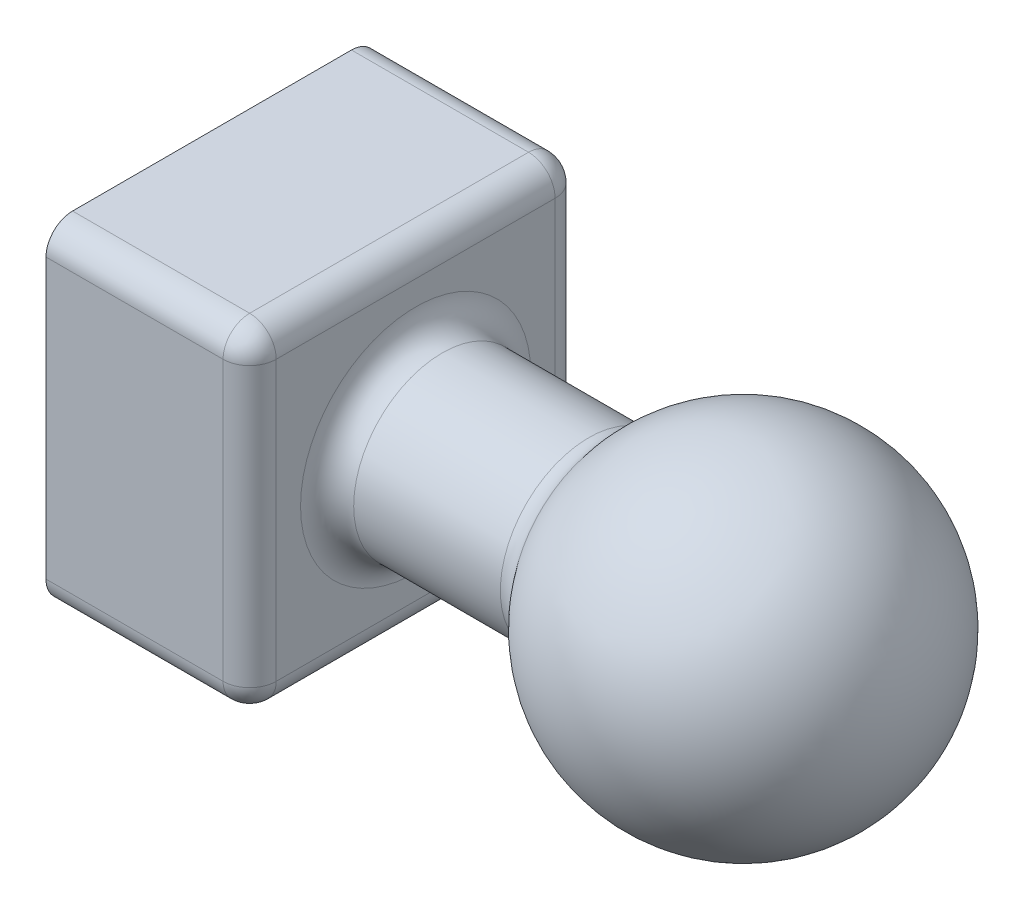
SolidWorks part; units mm, degrees
ref_plane "Front Plane" through (0, 0, 0) normal (0, 0, 1) x (1, 0, 0)
ref_plane "Top Plane" through (0, 0, 0) normal (0, 1, 0) x (1, 0, 0)
ref_plane "Right Plane" through (0, 0, 0) normal (1, 0, 0) x (0, 0, -1)
sketch "Sketch1" plane through (0, 0, 0) normal (0, 0, 1) x (1, 0, 0)
  line L0 (0, 0) -> (55.75, 0) construction
  line L1 (0, 0) -> (0, 10) construction
  line L2 (0, 10) -> (21.1393, 10)
  line L7 (0, 10) -> (0, 0)
  line L8 (0, 0) -> (55.75, 0)
  line L9 (55.75, 0) -> (-119.6805, 0) construction
  line L10 (37, 18.75) -> (-31.2433, 18.75) construction
  arc A0 (55.75, 0) -> (21.1393, 10) centre (37, 0) ccw
  point P7 (-3.7507, 10)
  point P12 (-4.1632, 18.75)
  point P13 (0, 0)
  point P14 (-0.4506, 10)
  dimension "D1" = 18.75
  dimension "D2" = 37
  dimension "D3" = 20
revolve "Revolve1" add sketch "Sketch1" angle 360 about L9
sketch "Sketch2" plane through (0, 0, 0) normal (-1, 0, 0) x (0, 0, 1)
  line L1 (-18.75, -18.75) -> (18.75, -18.75)
  line L2 (-18.75, -18.75) -> (-18.75, 18.75)
  line L3 (-18.75, 18.75) -> (18.75, 18.75)
  line L4 (18.75, -18.75) -> (18.75, 18.75)
  line L5 (-18.75, -18.75) -> (18.75, 18.75) construction
  line L6 (-18.75, 18.75) -> (18.75, -18.75) construction
  circle A1 centre (0, 0) radius 15
  circle A2 centre (0, 0) radius 18.75 construction
  point P0 (0, 0)
  dimension "D1" = 30
extrude "Boss-Extrude1" add sketch "Sketch2" along normal blind 23
sketch "Sketch3" plane through (0, 0, 0) normal (-1, 0, 0) x (0, 0, 1)
  circle A0 centre (0, 0) radius 15 construction
  circle A1 centre (0, 0) radius 15
extrude "Boss-Extrude2" add sketch "Sketch3" along normal blind 3
sketch "Sketch4" plane through (-23, 0, 0) normal (-1, 0, 0) x (0, 0, 1)
  line L4 (0, 0) -> (-39.0127, 39.0127) construction
  line L5 (-39.5431, 38.4824) -> (-38.4824, 39.5431)
  line L6 (-39.5431, 38.4824) -> (-10.0916, 9.0309)
  line L7 (-38.4824, 39.5431) -> (-9.0309, 10.0916)
  line L8 (-10.0916, 9.0309) -> (-9.0309, 10.0916)
  point P2 (-18.75, 18.75)
  point P3 (0, 0)
  dimension "D1" = 1.5
extrude "Cut-Extrude1" [suppressed] cut sketch "Sketch4" against normal up to surface (17 mm away)
sketch "Sketch5" [suppressed] plane through (-20, 0, 0) normal (-1, 0, 0) x (0, 0, 1)
  line L0 (0, 0) -> (-18.75, 18.75) construction
  line L1 (-17.6893, 18.75) -> (-28.2959, 29.3566)
  line L2 (-28.2959, 29.3566) -> (-26.8817, 30.7708)
  line L3 (-26.8817, 30.7708) -> (-14.8609, 18.75)
  line L4 (18.75, 18.75) -> (-17.6893, 18.75) construction
  line L5 (-17.6893, 18.75) -> (-14.8609, 18.75)
  line L6 (-10.0984, 11.1591) -> (-17.6893, 18.75) construction
  line L7 (-7.7898, 18.75) -> (-18.3964, 29.3566) construction
  line L8 (-29.3566, 28.2959) -> (-30.7708, 26.8817)
  line L9 (-18.75, 17.6893) -> (-29.3566, 28.2959)
  line L10 (-18.75, 17.6893) -> (-18.75, 14.8609)
  line L11 (-30.7708, 26.8817) -> (-18.75, 14.8609)
  point P15 (-27.486, 31.3751)
  dimension "D1" = 2
  dimension "D2" = 5
  dimension "D3" = 15
  dimension "D4" = 7
extrude "Boss-Extrude3" [suppressed] add sketch "Sketch5" against normal blind 8
fillet "Fillet2" radius 3 10 edges at (-11.5, -18.75, -18.75) (-11.5, 18.75, 18.75) (-11.5, -18.75, 18.75) (0, 0, -18.75) (0, -18.75, 0) (0, 18.75, 0) (0, 0, 18.75) (0, 0, -10) (21.1393, 0, -10) (-11.5, 18.75, -18.75)
fillet "Fillet3" radius 2 1 edges at (-23, 0, 15)
